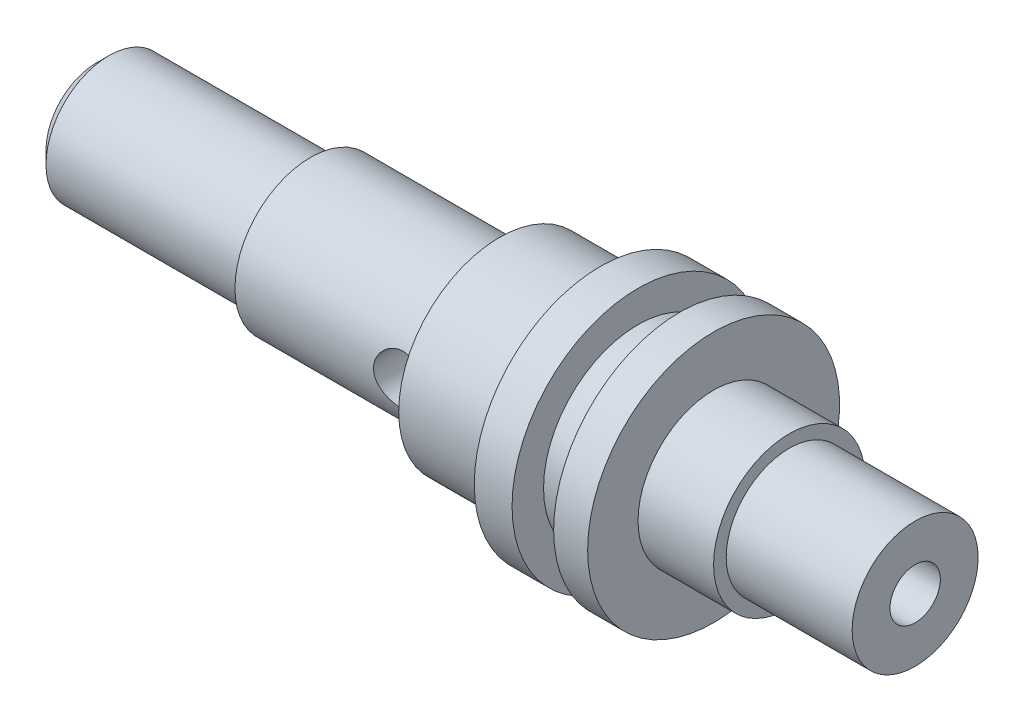
SolidWorks part; units mm, degrees
ref_plane "Спереди" through (0, 0, 0) normal (0, 0, 1) x (1, 0, 0)
ref_plane "Сверху" through (0, 0, 0) normal (0, 1, 0) x (1, 0, 0)
ref_plane "Справа" through (0, 0, 0) normal (1, 0, 0) x (0, 0, -1)
sketch "Эскиз1" plane through (0, 0, 0) normal (0, 0, 1) x (1, 0, 0)
  line L0 (0, 0) -> (130.6621, 0) construction
  line L1 (0, 0) -> (0, 5)
  line L2 (0, 5) -> (17, 5)
  line L3 (17, 5) -> (17, 6)
  line L4 (17, 6) -> (32, 6)
  line L5 (32, 6) -> (32, 8)
  line L6 (32, 8) -> (40, 8)
  line L7 (40, 8) -> (40, 10)
  line L8 (40, 10) -> (43, 10)
  line L9 (43, 10) -> (43, 7.5)
  line L10 (43, 7.5) -> (46.3, 7.5)
  line L11 (46.3, 7.5) -> (46.3, 10)
  line L12 (46.3, 10) -> (49, 10)
  line L13 (49, 10) -> (49, 6)
  line L14 (49, 6) -> (55, 6)
  line L15 (55, 6) -> (55, 5)
  line L16 (55, 5) -> (65, 5)
  line L17 (65, 5) -> (65, 2)
  line L18 (65, 2) -> (25, 2)
  line L19 (25, 2) -> (23.8453, 0)
  line L20 (23.8453, 0) -> (0, 0)
  dimension "D1" = 60
  dimension "D2" = 4
  dimension "D3" = 10
  dimension "D4" = 17
  dimension "D5" = 12
  dimension "D6" = 16
  dimension "D7" = 20
  dimension "D8" = 32
  dimension "D9" = 40
  dimension "D10" = 3.3
  dimension "D11" = 15
  dimension "D12" = 6
  dimension "D13" = 10
  dimension "D14" = 65
  dimension "D15" = 9
  dimension "D16" = 40
  dimension "D17" = 10
revolve "Повернуть1" add sketch "Эскиз1" angle 360 about L0
cosmetic thread "Условное изображение резьбы1" parameters "D1"=15, "D2"=8.917
sketch "Эскиз2" plane through (0, 0, 0) normal (0, 0, 1) x (1, 0, 0)
  line L0 (65, -5) -> (65, 5) construction
  circle A0 centre (30, 0) radius 2
  dimension "D1" = 4
  dimension "D2" = 35
extrude "Вырез-Вытянуть1" cut sketch "Эскиз2" against normal through all both and the other way through all
chamfer "Фаска1" distance 1 angle 45 1 edges at (0, 0, 5)
